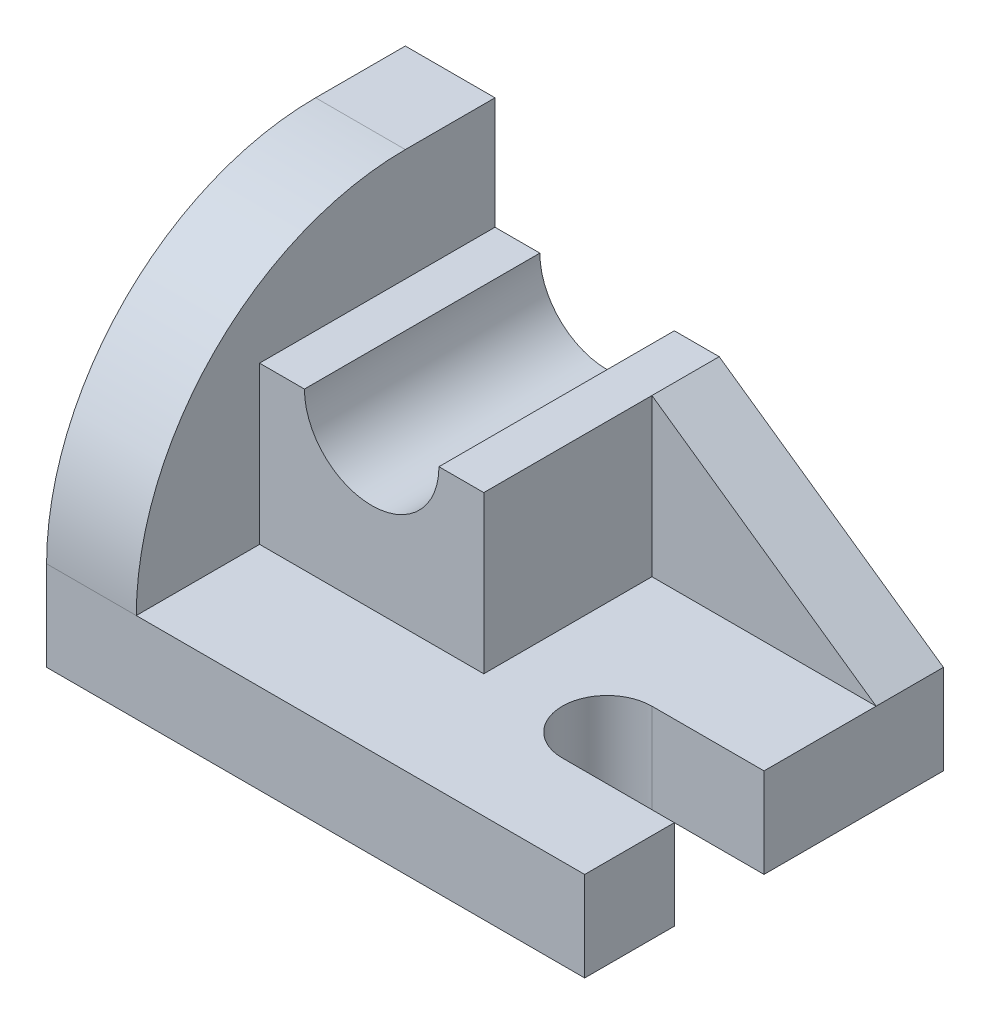
SolidWorks part; units mm, degrees
ref_plane "Ön Düzlem" through (0, 0, 0) normal (0, 0, 1) x (1, 0, 0)
ref_plane "Üst Düzlem" through (0, 0, 0) normal (0, 1, 0) x (1, 0, 0)
ref_plane "Sağ Düzlem" through (0, 0, 0) normal (1, 0, 0) x (0, 0, -1)
sketch "Sketch1" plane through (0, 0, 0) normal (0, 1, 0) x (1, 0, 0)
  line L1 (0, 0) -> (96, 0)
  line L2 (0, 0) -> (0, 64)
  line L3 (0, 64) -> (96, 64)
  line L4 (96, 0) -> (96, 64)
  dimension "D1" = 96
  dimension "D2" = 64
extrude "Boss-Extrude1" add sketch "Sketch1" along normal blind 16
sketch "Sketch2" plane through (0, 16, 0) normal (0, 1, 0) x (1, 0, 0)
  line L0 (96, 24) -> (76, 24) construction
  line L1 (96, 0) -> (96, 64) construction
  line L2 (96, 16) -> (76, 16)
  line L3 (96, 32) -> (76, 32)
  line L4 (0, 0) -> (96, 0) construction
  arc A0 (96, 16) -> (96, 32) centre (96, 24) ccw
  arc A1 (76, 32) -> (76, 16) centre (76, 24) ccw
  point P4 (86, 24)
  dimension "D2" = 8
  dimension "D1" = 20
  dimension "D3" = 16
extrude "Cut-Extrude1" cut sketch "Sketch2" against normal blind 16
sketch "Sketch3" plane through (0, 0, 0) normal (-1, 0, 0) x (0, 0, 1)
  line L1 (-64, 0) -> (0, 0)
  line L2 (-64, 0) -> (-64, 64)
  line L3 (-64, 64) -> (-48, 64)
  line L4 (0, 0) -> (0, 16)
  arc A0 (0, 16) -> (-48, 64) centre (-48, 16) ccw
  point P7 (0, 64)
  dimension "D3" = 48
  dimension "D1" = 64
  dimension "D2" = 64
extrude "Boss-Extrude2" add sketch "Sketch3" against normal blind 16
sketch "Sketch4" plane through (0, 16, 0) normal (0, 1, 0) x (1, 0, 0)
  line L0 (16, 0) -> (96, 0) construction
  line L1 (16, 64) -> (56, 64)
  line L2 (16, 64) -> (16, 22)
  line L3 (16, 22) -> (56, 22)
  line L4 (56, 64) -> (56, 22)
  dimension "D1" = 40
  dimension "D2" = 22
extrude "Boss-Extrude3" add sketch "Sketch4" along normal blind 28
sketch "Sketch5" plane through (0, 0, -22) normal (0, 0, 1) x (1, 0, 0)
  line L0 (16, 44) -> (56, 44) construction
  circle A0 centre (36, 44) radius 12
  dimension "D1" = 24
extrude "Cut-Extrude2" cut sketch "Sketch5" against normal up to next
sketch "Sketch7" plane through (0, 0, -64) normal (0, 0, -1) x (-1, 0, 0)
  line L0 (-56, 44) -> (-96, 16)
  line L10 (-16, 44) -> (-24, 44)
  line L11 (-48, 44) -> (-56, 44)
  line L12 (-56, 44) -> (-56, 16)
  line L13 (-56, 16) -> (-96, 16)
  line L14 (-96, 16) -> (-96, 0)
  line L15 (-96, 0) -> (0, 0)
  line L16 (0, 0) -> (0, 64)
  line L17 (0, 64) -> (-16, 64)
  line L18 (-16, 64) -> (-16, 44)
  line L21 (-56, 44) -> (-56, 16)
  line L22 (-56, 16) -> (-96, 16)
  arc A1 (-48, 44) -> (-24, 44) centre (-36, 44) ccw
  dimension "D1" = 0
extrude "Boss-Extrude4" add sketch "Sketch7" against normal blind 12
